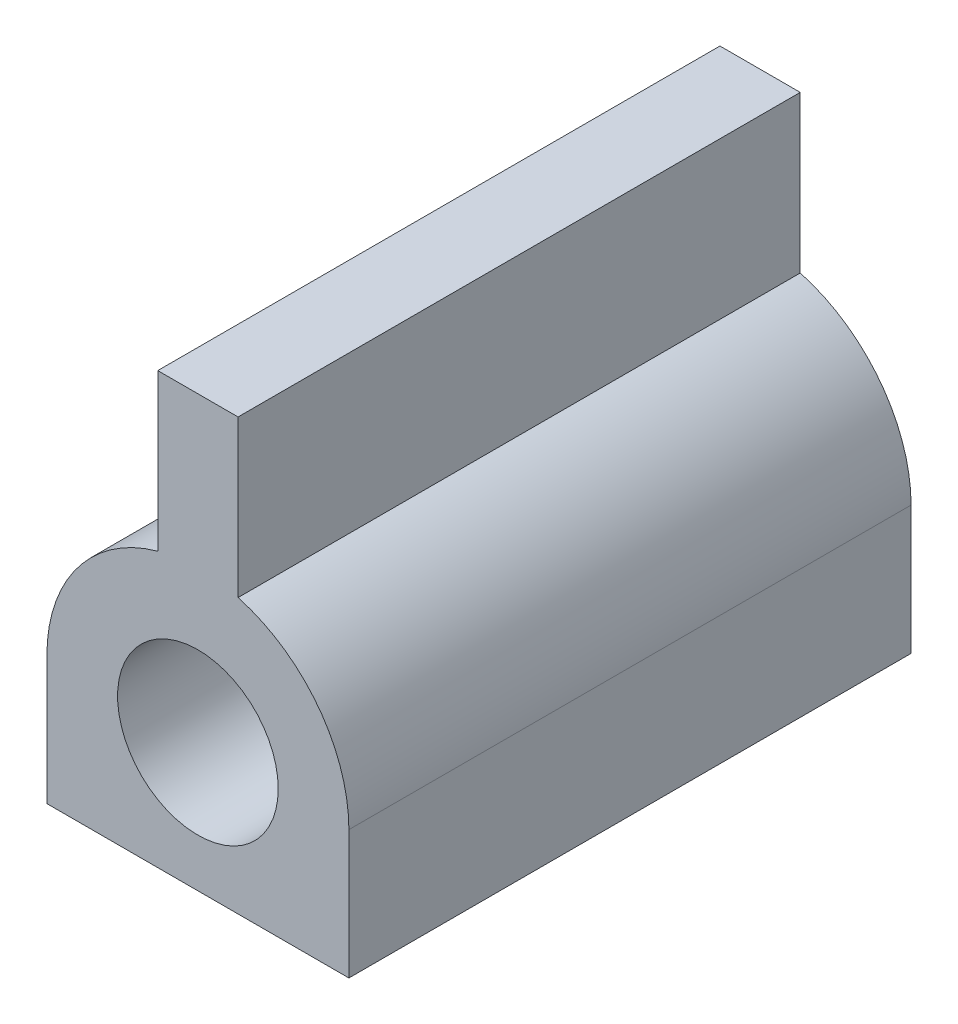
SolidWorks part; units mm, degrees
ref_plane "Front Plane" through (0, 0, 0) normal (0, 0, 1) x (1, 0, 0)
ref_plane "Top Plane" through (0, 0, 0) normal (0, 1, 0) x (1, 0, 0)
ref_plane "Right Plane" through (0, 0, 0) normal (1, 0, 0) x (0, 0, -1)
sketch "Sketch1" plane through (0, 0, 0) normal (0, 0, 1) x (1, 0, 0)
  line L0 (11.938, -10.16) -> (-11.938, -10.16)
  line L1 (-11.938, -10.16) -> (-11.938, 0)
  line L2 (11.938, 0) -> (11.938, -10.16)
  line L3 (-3.175, 11.5081) -> (-3.175, 23.876)
  line L4 (-3.175, 23.876) -> (3.175, 23.876)
  line L5 (3.175, 23.876) -> (3.175, 11.5081)
  line L6 (0, 23.876) -> (0, -10.16) construction
  arc A0 (-11.938, 0) -> (-3.175, 11.5081) centre (0, 0) cw
  circle A1 centre (0, 0) radius 6.35
  arc A2 (3.175, 11.5081) -> (11.938, 0) centre (0, 0) cw
  dimension "D1" = 12.7
  dimension "D2" = 23.876
  dimension "D3" = 34.036
  dimension "D4" = 10.16
  dimension "D5" = 6.35
extrude "Boss-Extrude1" add sketch "Sketch1" along normal mid plane 44.45
